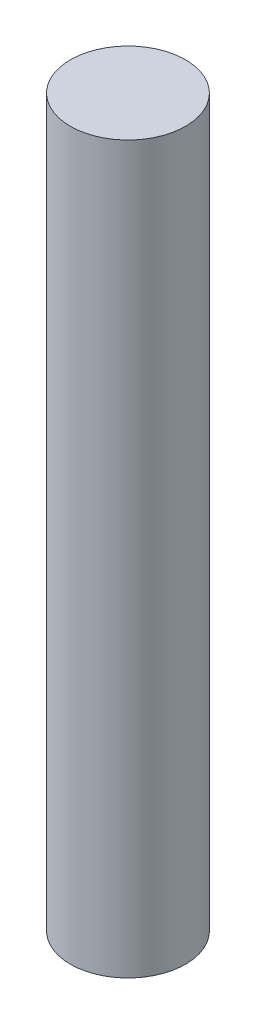
SolidWorks part; units mm, degrees
material "AISI 1045 Steel, cold drawn"
ref_plane "Front Plane" through (0, 0, 0) normal (0, 0, 1) x (1, 0, 0)
ref_plane "Top Plane" through (0, 0, 0) normal (0, 1, 0) x (1, 0, 0)
ref_plane "Right Plane" through (0, 0, 0) normal (1, 0, 0) x (0, 0, -1)
sketch "Sketch1" plane through (0, 0, 0) normal (0, 1, 0) x (1, 0, 0)
  circle A0 centre (0, 0) radius 4.7625
  dimension "D1" = 9.525
extrude "Boss-Extrude1" add sketch "Sketch1" along normal blind 60
